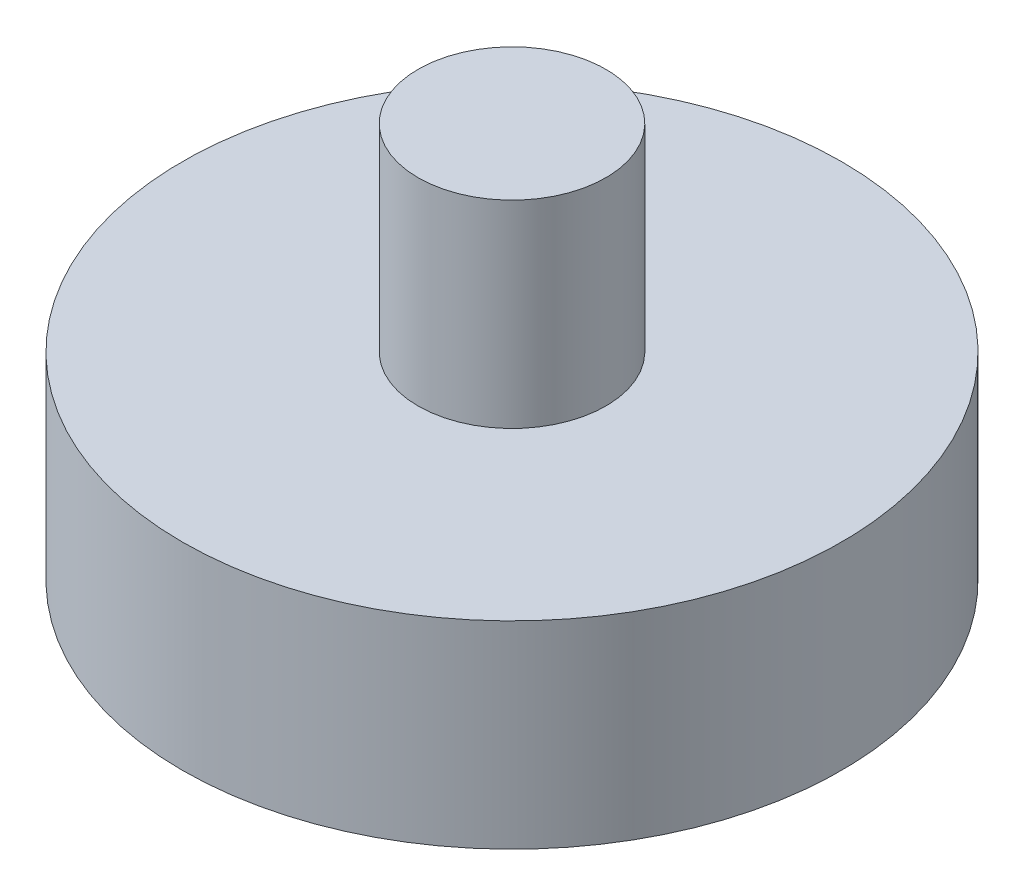
SolidWorks part; units mm, degrees
ref_plane "Alzado" through (0, 0, 0) normal (0, 0, 1) x (1, 0, 0)
ref_plane "Planta" through (0, 0, 0) normal (0, 1, 0) x (1, 0, 0)
ref_plane "Vista lateral" through (0, 0, 0) normal (1, 0, 0) x (0, 0, -1)
sketch "Croquis2" plane through (0, 0, 0) normal (0, 1, 0) x (1, 0, 0)
  circle A0 centre (0, 0) radius 5
  dimension "D1" = 10
extrude "Saliente-Extruir1" add sketch "Croquis2" along normal blind 3
sketch "Croquis3" plane through (0, 3, 0) normal (0, 1, 0) x (1, 0, 0)
  circle A0 centre (0, 0) radius 1.425
  dimension "D1" = 2.85
extrude "Saliente-Extruir2" add sketch "Croquis3" along normal blind 3
